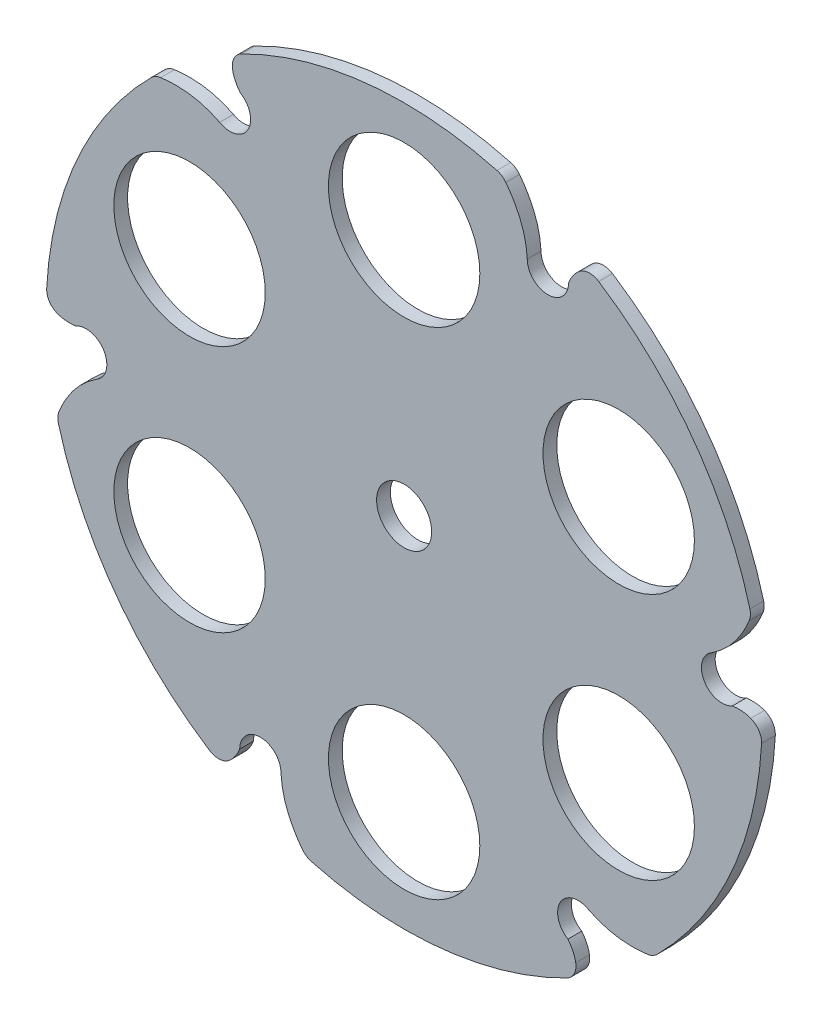
SolidWorks part; units mm, degrees
material "6061 Alloy"
ref_plane "Front Plane" through (0, 0, 0) normal (0, 0, 1) x (1, 0, 0)
ref_plane "Top Plane" through (0, 0, 0) normal (0, 1, 0) x (1, 0, 0)
ref_plane "Right Plane" through (0, 0, 0) normal (1, 0, 0) x (0, 0, -1)
sketch "Sketch1" plane through (0, 0, 0) normal (0, 0, 1) x (1, 0, 0)
  circle A0 centre (0, 114.3) radius 34.925
  circle A1 centre (98.9867, 57.15) radius 34.925
  circle A2 centre (98.9867, -57.15) radius 34.925
  circle A3 centre (0, -114.3) radius 34.925
  circle A4 centre (-98.9867, -57.15) radius 34.925
  circle A5 centre (-98.9867, 57.15) radius 34.925
  circle A6 centre (0, 0) radius 165.1
  circle A7 centre (0, 0) radius 12.7
  point P16 (0, 0)
  point P27 (0, -10.16)
  point P76 (0, 0)
  dimension "D1" = 69.85
  dimension "D4" = 330.2
  dimension "D10" = 114.3
  dimension "D3" = 6
extrude "Boss-Extrude1" add sketch "Sketch1" along normal mid plane 6.35
sketch "Sketch2" plane through (0, 0, 3.175) normal (0, 0, 1) x (1, 0, 0)
  line L0 (-75.8571, -131.064) -> (-56.8071, -131.064) construction
  circle A0 centre (-66.3321, -131.064) radius 9.525
  circle A2 centre (0, -114.3) radius 34.925 construction
  circle A3 centre (0, 0) radius 165.1 construction
  circle A4 centre (0, -114.3) radius 34.925 construction
  spline S0 degree 2 poles (-75.8571, -131.064) (-78.7535, -138.4295) (-85.9715, -140.95) knots 0 0 0 1 1 1
  spline S1 degree 2 poles (-56.8071, -131.064) (-56.0987, -145.8213) (-45.253, -158.7771) knots 0 0 0 1 1 1
  circle M4 centre (0, 0) radius 165.1
  dimension "D1" = 66.3321
  dimension "D2" = 19.05
  dimension "D4" = 16.764
  dimension "D3" = 44.45
  dimension "D5" = 30.0252
extrude "Cut-Extrude1" cut sketch "Sketch2" against normal through all contours A0 L0 | L0 A0 | S1 A0 S0 M4
pattern_circular "CirPattern1" count 6 over 360 about axis through (0, 0, 3.175) along (0, 0, 1) of "Cut-Extrude1"
fillet "Fillet1" radius 7.62 12 edges at (79.0805, -144.9285, 0) (114.8785, -118.5788, 0) (165.0521, -3.9785, 0) (160.1315, 40.1983, 0) (85.9715, 140.95, 0) (45.253, 158.7771, 0) (-114.8785, 118.5788, 0) (-79.0805, 144.9285, 0) (-165.0521, 3.9785, 0) (-160.1315, -40.1983, 0) (-45.253, -158.7771, 0) (-85.9715, -140.95, 0)
